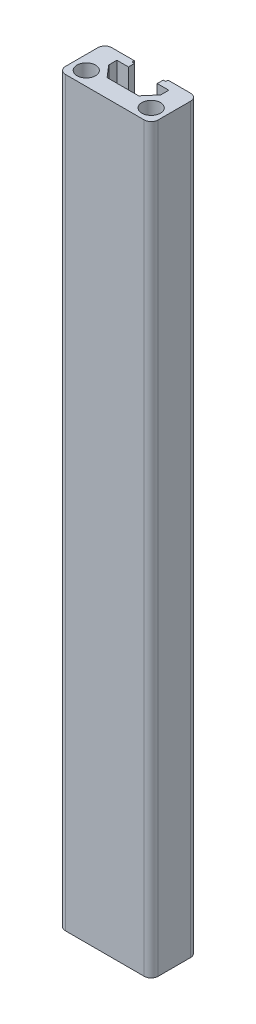
SolidWorks part; units mm, degrees
ref_plane "前视基准面" through (0, 0, 0) normal (0, 0, 1) x (1, 0, 0)
ref_plane "上视基准面" through (0, 0, 0) normal (0, 1, 0) x (1, 0, 0)
ref_plane "右视基准面" through (0, 0, 0) normal (1, 0, 0) x (0, 0, -1)
sketch "草图1" plane through (0, 0, 0) normal (0, 1, 0) x (1, 0, 0)
  line L0 (0, 0) -> (20, 0)
  line L1 (20, 0) -> (20, 10)
  line L2 (20, 10) -> (13.65, 10)
  line L3 (0, 10) -> (0, 0)
  line L4 (6.35, 10) -> (6.35, 9.5104)
  line L5 (6.35, 9.5104) -> (6.9, 9.5104)
  line L6 (6.9, 9.5104) -> (6.9, 8.2)
  line L7 (6.9, 8.2) -> (4.4, 8.2)
  line L8 (4.4, 8.2) -> (4.4, 6.4475)
  line L9 (4.4, 6.4475) -> (6.5873, 3.9)
  line L11 (15.6, 6.4475) -> (15.6, 8.2)
  line L12 (15.6, 8.2) -> (13.1, 8.2)
  line L13 (13.1, 8.2) -> (13.1, 9.5104)
  line L14 (13.1, 9.5104) -> (13.65, 9.5104)
  line L15 (13.65, 9.5104) -> (13.65, 10)
  line L16 (6.35, 10) -> (0, 10)
  line L17 (10, 0) -> (10, 13.7687) construction
  line L18 (6.5873, 3.9) -> (13.4127, 3.9)
  line L19 (13.4127, 3.9) -> (15.6, 6.4475)
  circle A0 centre (3, 3) radius 2
  circle A1 centre (17, 3) radius 2
  point P12 (10, 3.9)
  dimension "D8" = 4
  dimension "D1" = 20
  dimension "D2" = 10
  dimension "D3" = 7.3
  dimension "D4" = 6.2
  dimension "D5" = 1.8
  dimension "D6" = 4.3
  dimension "D7" = 11.2
  dimension "D9" = 3
  dimension "D10" = 14
extrude "凸台-拉伸1" add sketch "草图1" along normal blind 160
fillet "圆角1" radius 1.5 4 edges at (0, 80, -10) (0, 80, 0) (20, 80, -10) (20, 80, 0)
